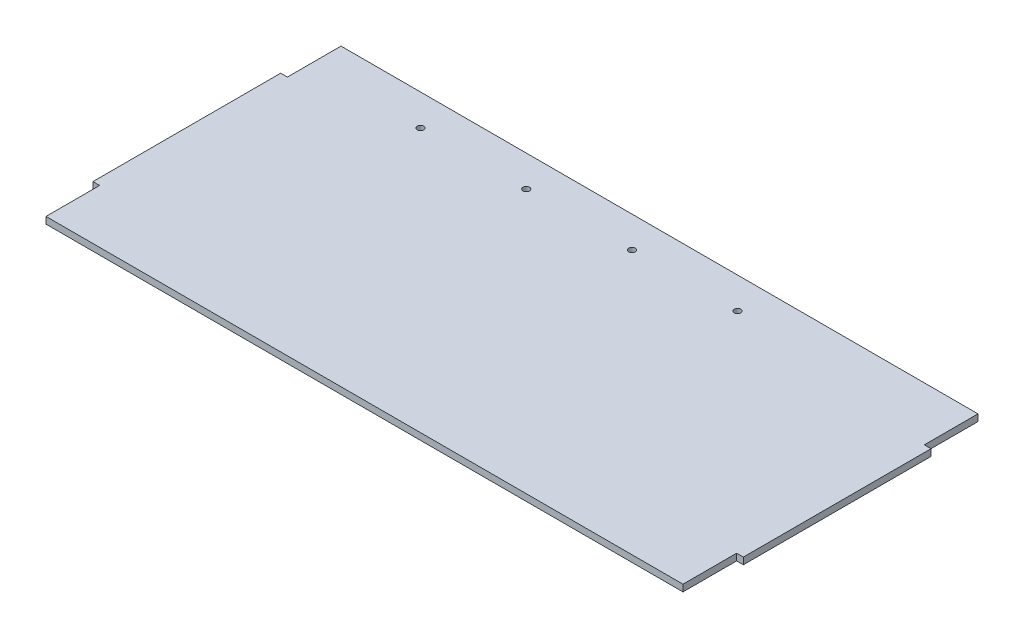
SolidWorks part; units mm, degrees
other "Markup1"
sketch "Sketch2" plane through (-342.9, 3.175, 69.85) normal (-0.3389, 0.9284, 0.1524) x (0.9392, 0.3243, 0.1131)
material "Balsa"
ref_plane "Front Plane" through (0, 0, 0) normal (0, 0, 1) x (1, 0, 0)
ref_plane "Top Plane" through (0, 0, 0) normal (0, 1, 0) x (1, 0, 0)
ref_plane "Right Plane" through (0, 0, 0) normal (1, 0, 0) x (0, 0, -1)
sketch "Sketch1" plane through (0, 0, 0) normal (0, 1, 0) x (1, 0, 0)
  line L0 (-150.8125, 44.45) -> (-153.9875, 44.45)
  line L1 (-150.8125, -69.85) -> (150.8125, -69.85)
  line L2 (-150.8125, -69.85) -> (-150.8125, -44.45)
  line L3 (-150.8125, 69.85) -> (150.8125, 69.85)
  line L4 (150.8125, -69.85) -> (150.8125, -44.45)
  line L5 (-150.8125, -69.85) -> (150.8125, 69.85) construction
  line L6 (-150.8125, 69.85) -> (150.8125, -69.85) construction
  line L7 (-153.9875, 44.45) -> (-153.9875, -44.45)
  line L8 (-153.9875, -44.45) -> (-150.8125, -44.45)
  line L9 (-150.8125, 44.45) -> (-150.8125, 69.85)
  line L10 (150.8125, 44.45) -> (153.9875, 44.45)
  line L11 (153.9875, 44.45) -> (153.9875, -44.45)
  line L12 (153.9875, -44.45) -> (150.8125, -44.45)
  line L13 (150.8125, 44.45) -> (150.8125, 69.85)
  point P0 (0, 0)
  dimension "D1" = 139.7
  dimension "D2" = 301.625
  dimension "D3" = 25.4
  dimension "D4" = 25.4
  dimension "D5" = 3.175
  dimension "D6" = 3.175
  dimension "D7" = 25.4
  dimension "D8" = 25.4
extrude "Boss-Extrude1" add sketch "Sketch1" along normal blind 3.175
sketch "Sketch3" plane through (0, 3.175, 0) normal (0, 1, 0) x (1, 0, 0)
  line L0 (-150.8125, 69.85) -> (-150.8125, 44.45) construction
  line L1 (150.8125, 69.85) -> (-150.8125, 69.85) construction
  circle A0 centre (-98.3704, 55.0878) radius 1.5494
  circle A1 centre (-48.3324, 55.0878) radius 1.5494
  circle A2 centre (1.7056, 55.0878) radius 1.5494
  circle A3 centre (51.7436, 55.0878) radius 1.5494
  dimension "D1" = 3.0988
  dimension "D3" = 14.7622
  dimension "D2" = 52.4421
  dimension "D4" = 4
extrude "Cut-Extrude1" cut sketch "Sketch3" against normal through all
